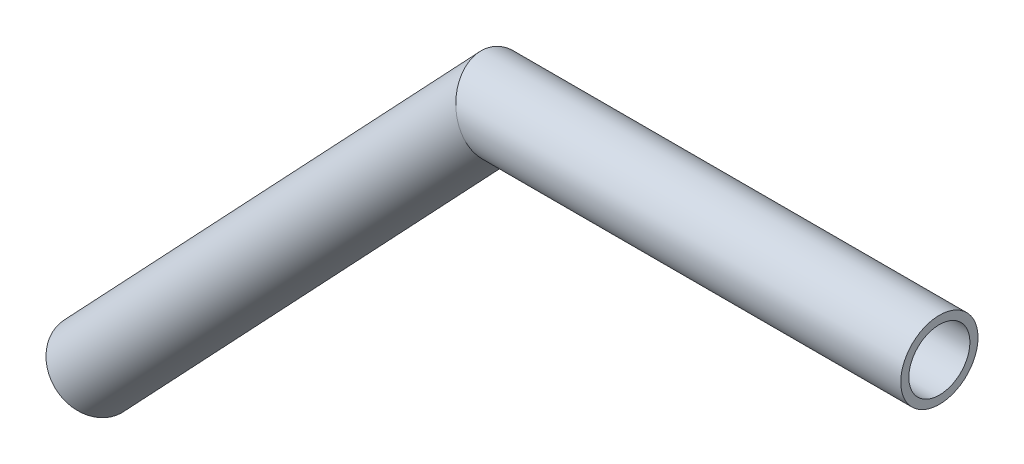
SolidWorks part; units mm, degrees
material "Plain Carbon Steel"
ref_plane "Front Plane" through (0, 0, 0) normal (0, 0, 1) x (1, 0, 0)
ref_plane "Top Plane" through (0, 0, 0) normal (0, 1, 0) x (1, 0, 0)
ref_plane "Right Plane" through (0, 0, 0) normal (1, 0, 0) x (0, 0, -1)
sketch "Sketch1" plane through (0, 0, 0) normal (1, 0, 0) x (0, 0, -1)
  circle A0 centre (0, 0) radius 13.335
  circle A1 centre (0, 0) radius 10.541
  dimension "D2" = 26.67
  dimension "D1" = 2.794
sketch "Sketch2" plane through (0, 0, 0) normal (0, 0, 1) x (1, 0, 0)
  line L0 (0, 0) -> (-152.4, 0)
  line L1 (-152.4, 0) -> (-291.8873, -147.7618)
  dimension "D1" = 152.4
  dimension "D2" = 203.2
  dimension "D3" = 133.35
sweep "Sweep1" add profiles "Sketch1" path "Sketch2"
ref_plane "Plane1" through (-128.5077, -55.4107, 0) normal (0.9183, 0.3959, 0) x (0, 0, -1)
sketch "Sketch3" plane through (-128.5077, -55.4107, 0) normal (0.9183, 0.3959, 0) x (0, 0, -1)
  line L0 (0, 60.3422) -> (0, 150.5454) construction
  circle A0 centre (0, 60.3422) radius 14.5218 construction
